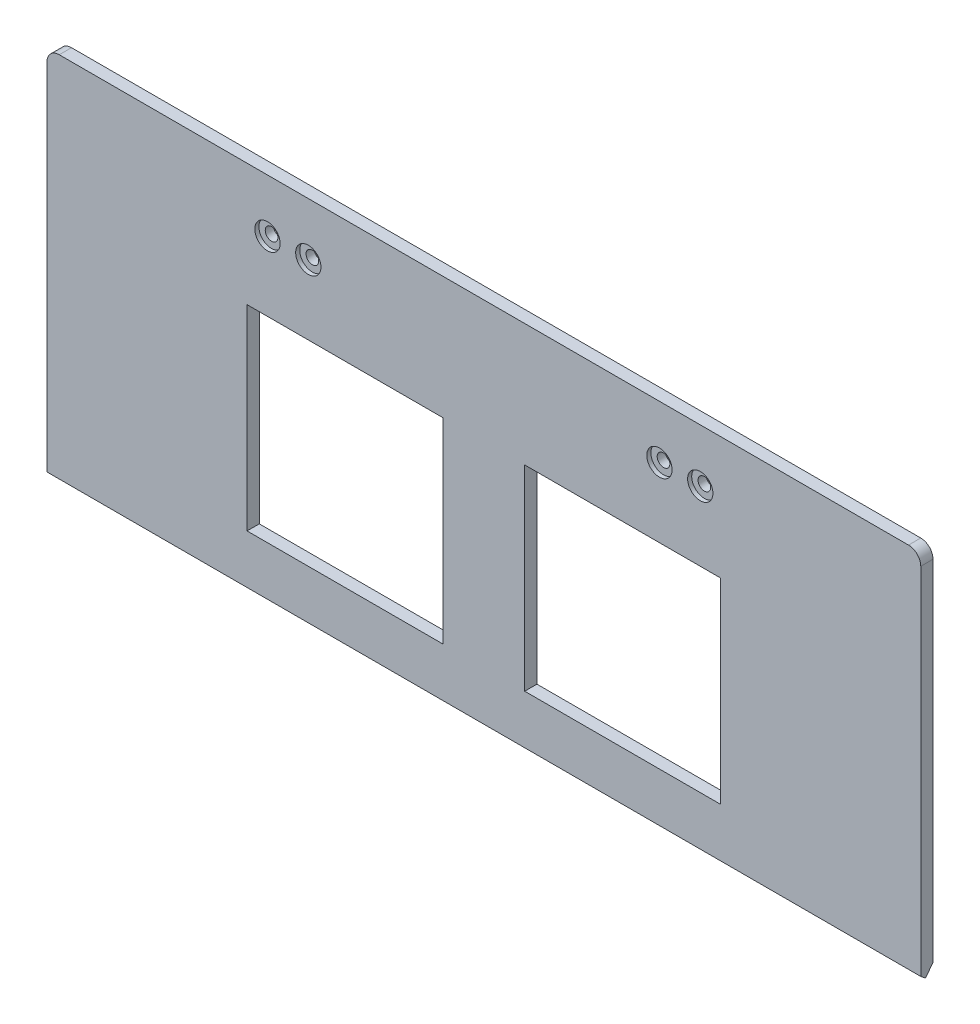
SolidWorks part; units mm, degrees
ref_plane "前视基准面" through (0, 0, 0) normal (0, 0, 1) x (1, 0, 0)
ref_plane "上视基准面" through (0, 0, 0) normal (0, 1, 0) x (1, 0, 0)
ref_plane "右视基准面" through (0, 0, 0) normal (1, 0, 0) x (0, 0, -1)
other "Configuration Table"
sketch "草图2" plane through (0, 0, 0) normal (0, 0, 1) x (1, 0, 0)
  line L1 (-107, 45) -> (107, 45)
  line L2 (-107, 45) -> (-107, -45)
  line L3 (-107, -45) -> (107, -45)
  line L4 (107, 45) -> (107, -45)
  line L5 (0, -45) -> (0, 45) construction
  line L6 (-107, 0) -> (107, 0) construction
  point P0 (0, 0)
  dimension "D1" = 214
  dimension "D2" = 90
sketch "草图11" plane through (0, 0, -3) normal (0, 0, -1) x (-1, 0, 0)
  line L1 (-58, 15) -> (-10, 15)
  line L2 (-58, 15) -> (-58, -33)
  line L3 (-58, -33) -> (-10, -33)
  line L4 (-10, 15) -> (-10, -33)
  line L5 (10, 15) -> (58, 15)
  line L6 (10, 15) -> (10, -33)
  line L7 (10, -33) -> (58, -33)
  line L8 (58, 15) -> (58, -33)
  dimension "D1" = 48
  dimension "D2" = 48
  dimension "D3" = 48
  dimension "D4" = 48
sketch "草图13" plane through (0, -24.1238, 18.8476) normal (0, 0.788, -0.6157) x (1, 0, 0)
  circle A0 centre (55.5, 40.2772) radius 1.75
  circle A1 centre (18.5, 40.2772) radius 1.75
  circle A2 centre (-18.5, 40.2772) radius 1.75
  circle A4 centre (-55.5, 40.2772) radius 1.75
sketch "草图14" plane through (0, 0, -3) normal (0, 0, -1) x (-1, 0, 0)
  circle A0 centre (-53, 32) radius 1.55
  circle A1 centre (-43, 32) radius 1.55
  circle A2 centre (43, 32) radius 1.55
  circle A3 centre (53, 32) radius 1.55
sketch "草图15" plane through (0, 0, 0) normal (0, 0, 1) x (1, 0, 0)
  circle A0 centre (53, 32) radius 3.1
  circle A1 centre (43, 32) radius 3.1
  circle A2 centre (-43, 32) radius 3.1
  circle A3 centre (-53, 32) radius 3.1
  dimension "D1" = 6.2
  dimension "D2" = 6.2
  dimension "D3" = 6.2
  dimension "D4" = 6.2
extrude "凸台-拉伸5" add sketch "草图2" against normal blind 3
extrude "切除-拉伸12" cut sketch "草图14" against normal through all
extrude "切除-拉伸14" cut sketch "草图15" against normal blind 1
extrude "切除-拉伸15" cut sketch "草图11" against normal through all
sketch "草图21" plane through (107, 0, 0) normal (1, 0, 0) x (0, 0, -1)
  line L3 (0, -45) -> (19.9871, -60.6157)
  line L4 (0, -45) -> (3, -45)
  line L5 (21.1242, -59.1602) -> (19.9871, -60.6157)
  line L6 (3, -45) -> (21.1242, -59.1602)
  dimension "D2" = 23
extrude "凸台-拉伸6" add sketch "草图21" against normal through all
sketch "草图22" plane through (107, 0, 0) normal (1, 0, 0) x (0, 0, -1)
  line L0 (3, -43.5406) -> (21.8323, -58.254)
  line L1 (3, -45) -> (3, 45) construction
  line L2 (21.1242, -59.1602) -> (3, -45) construction
  line L3 (21.1242, -59.1602) -> (21.8323, -58.254)
  line L4 (3, -43.5406) -> (3, -45)
  line L5 (3, -45) -> (21.1242, -59.1602)
  dimension "D1" = 1.15
extrude "凸台-拉伸7" add sketch "草图22" against normal through all
extrude "切除-拉伸16" cut sketch "草图13" against normal through all
sketch "草图23" plane through (0, -25.5816, 19.9865) normal (0, 0.788, -0.6157) x (1, 0, 0)
  line L0 (-107, 29.1703) -> (107, 29.1703) construction
  line L1 (-107, 53.0688) -> (-72, 53.0688)
  line L2 (-107, 53.0688) -> (-107, 29.1703)
  line L3 (-107, 29.1703) -> (-72, 29.1703)
  line L4 (-72, 53.0688) -> (-72, 29.1703)
  line L5 (-107, 53.0688) -> (107, 53.0688) construction
  line L6 (107, 53.0688) -> (72, 53.0688)
  line L7 (107, 53.0688) -> (107, 29.1703)
  line L8 (107, 29.1703) -> (72, 29.1703)
  line L9 (72, 53.0688) -> (72, 29.1703)
  line L10 (107, 53.0688) -> (107, 29.1703) construction
  dimension "D1" = 35
  dimension "D2" = 35
extrude "切除-拉伸17" cut sketch "草图23" against normal through all
fillet "圆角3" radius 3 1 edges at (-107, 45, -1.5)
fillet "圆角4" radius 3 1 edges at (107, 45, -1.5)
